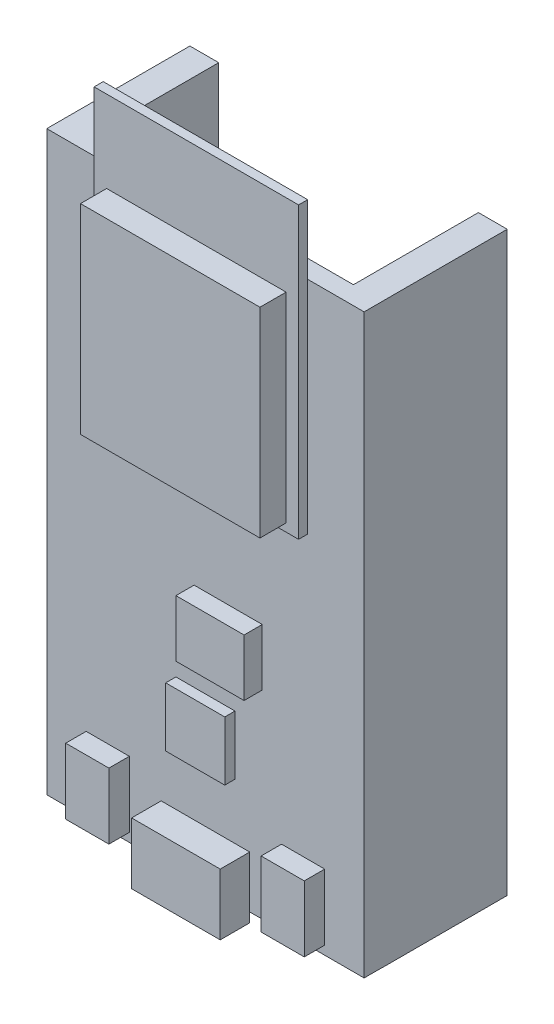
SolidWorks part; units mm, degrees
ref_plane "Front Plane" through (0, 0, 0) normal (0, 0, 1) x (1, 0, 0)
ref_plane "Top Plane" through (0, 0, 0) normal (0, 1, 0) x (1, 0, 0)
ref_plane "Right Plane" through (0, 0, 0) normal (1, 0, 0) x (0, 0, -1)
ref_plane "Plane1" through (0, 0, 10.6) normal (0, 0, 1) x (1, 0, 0)
sketch "Sketch1" plane through (0, 0, 10.6) normal (0, 0, 1) x (1, 0, 0)
  line L1 (-30.97, 19.02) -> (-28.43, 19.02)
  line L2 (-30.97, 19.02) -> (-30.97, 69.82)
  line L3 (-30.97, 69.82) -> (-28.43, 69.82)
  line L4 (-28.43, 19.02) -> (-28.43, 69.82)
  line L5 (-30.97, 19.02) -> (-28.43, 69.82) construction
  line L6 (-30.97, 69.82) -> (-28.43, 19.02) construction
  point P0 (-29.7, 44.42)
extrude "Boss-Extrude1" add sketch "Sketch1" along normal blind 8.5
ref_plane "Plane2" through (0, 0, 19.1) normal (0, 0, 1) x (1, 0, 0)
sketch "Sketch2" plane through (0, 0, 19.1) normal (0, 0, 1) x (1, 0, 0)
  line L1 (-30.97, 19.02) -> (-28.43, 19.02)
  line L2 (-30.97, 19.02) -> (-30.97, 69.82)
  line L3 (-30.97, 69.82) -> (-28.43, 69.82)
  line L4 (-28.43, 19.02) -> (-28.43, 69.82)
  line L5 (-30.97, 19.02) -> (-28.43, 69.82) construction
  line L6 (-30.97, 69.82) -> (-28.43, 19.02) construction
  point P0 (-29.7, 44.42)
extrude "Boss-Extrude2" add sketch "Sketch2" along normal blind 2.5
sketch "Sketch3" plane through (0, 0, 10.6) normal (0, 0, 1) x (1, 0, 0)
  line L1 (-5.57, 19.02) -> (-3.03, 19.02)
  line L2 (-5.57, 19.02) -> (-5.57, 69.82)
  line L3 (-5.57, 69.82) -> (-3.03, 69.82)
  line L4 (-3.03, 19.02) -> (-3.03, 69.82)
  line L5 (-5.57, 19.02) -> (-3.03, 69.82) construction
  line L6 (-5.57, 69.82) -> (-3.03, 19.02) construction
  point P0 (-4.3, 44.42)
extrude "Boss-Extrude3" add sketch "Sketch3" along normal blind 8.5
sketch "Sketch4" plane through (0, 0, 19.1) normal (0, 0, 1) x (1, 0, 0)
  line L1 (-5.57, 19.02) -> (-3.03, 19.02)
  line L2 (-5.57, 19.02) -> (-5.57, 69.82)
  line L3 (-5.57, 69.82) -> (-3.03, 69.82)
  line L4 (-3.03, 19.02) -> (-3.03, 69.82)
  line L5 (-5.57, 19.02) -> (-3.03, 69.82) construction
  line L6 (-5.57, 69.82) -> (-3.03, 19.02) construction
  point P0 (-4.3, 44.42)
extrude "Boss-Extrude4" add sketch "Sketch4" along normal blind 2.5
ref_plane "Plane3" through (0, 0, 21.6) normal (0, 0, 1) x (1, 0, 0)
sketch "Sketch5" plane through (0, 0, 21.6) normal (0, 0, 1) x (1, 0, 0)
  line L1 (-30.97, 19.03) -> (-3.03, 19.03)
  line L2 (-30.97, 19.03) -> (-30.97, 69.82)
  line L3 (-30.97, 69.82) -> (-3.03, 69.82)
  line L4 (-3.03, 19.03) -> (-3.03, 69.82)
  line L5 (-30.97, 19.03) -> (-3.03, 69.82) construction
  line L6 (-30.97, 69.82) -> (-3.03, 19.03) construction
  point P0 (-17, 44.425)
extrude "Boss-Extrude5" add sketch "Sketch5" along normal blind 1.6
ref_plane "Plane4" through (0, 0, 23.2) normal (0, 0, 1) x (1, 0, 0)
sketch "Sketch6" plane through (0, 0, 23.2) normal (0, 0, 1) x (1, 0, 0)
  line L1 (-26, 50.39) -> (-8, 50.39)
  line L2 (-26, 50.39) -> (-26, 75.89)
  line L3 (-26, 75.89) -> (-8, 75.89)
  line L4 (-8, 50.39) -> (-8, 75.89)
  line L5 (-26, 50.39) -> (-8, 75.89) construction
  line L6 (-26, 75.89) -> (-8, 50.39) construction
  point P0 (-17, 63.14)
extrude "Boss-Extrude6" add sketch "Sketch6" along normal blind 0.8
ref_plane "Plane5" through (0, 0, 24) normal (0, 0, 1) x (1, 0, 0)
sketch "Sketch7" plane through (0, 0, 24) normal (0, 0, 1) x (1, 0, 0)
  line L1 (-24.9, 51.09) -> (-9.1, 51.09)
  line L2 (-24.9, 51.09) -> (-24.9, 68.69)
  line L3 (-24.9, 68.69) -> (-9.1, 68.69)
  line L4 (-9.1, 51.09) -> (-9.1, 68.69)
  line L5 (-24.9, 51.09) -> (-9.1, 68.69) construction
  line L6 (-24.9, 68.69) -> (-9.1, 51.09) construction
  point P0 (-17, 59.89)
extrude "Boss-Extrude7" add sketch "Sketch7" along normal blind 2.3
sketch "Sketch8" plane through (0, 0, 23.2) normal (0, 0, 1) x (1, 0, 0)
  line L1 (-20.9, 18.2) -> (-13.1, 18.2)
  line L2 (-20.9, 18.2) -> (-20.9, 23.6)
  line L3 (-20.9, 23.6) -> (-13.1, 23.6)
  line L4 (-13.1, 18.2) -> (-13.1, 23.6)
  line L5 (-20.9, 18.2) -> (-13.1, 23.6) construction
  line L6 (-20.9, 23.6) -> (-13.1, 18.2) construction
  point P0 (-17, 20.9)
extrude "Boss-Extrude8" add sketch "Sketch8" along normal blind 2.6
sketch "Sketch9" plane through (0, 0, 23.2) normal (0, 0, 1) x (1, 0, 0)
  line L1 (-27.5, 19.8) -> (-23.7, 19.8)
  line L2 (-27.5, 19.8) -> (-27.5, 25.6)
  line L3 (-27.5, 25.6) -> (-23.7, 25.6)
  line L4 (-23.7, 19.8) -> (-23.7, 25.6)
  line L5 (-27.5, 19.8) -> (-23.7, 25.6) construction
  line L6 (-27.5, 25.6) -> (-23.7, 19.8) construction
  point P0 (-25.6, 22.7)
extrude "Boss-Extrude9" add sketch "Sketch9" along normal blind 1.8
sketch "Sketch10" plane through (0, 0, 23.2) normal (0, 0, 1) x (1, 0, 0)
  line L1 (-10.3, 19.8) -> (-6.5, 19.8)
  line L2 (-10.3, 19.8) -> (-10.3, 25.6)
  line L3 (-10.3, 25.6) -> (-6.5, 25.6)
  line L4 (-6.5, 19.8) -> (-6.5, 25.6)
  line L5 (-10.3, 19.8) -> (-6.5, 25.6) construction
  line L6 (-10.3, 25.6) -> (-6.5, 19.8) construction
  point P0 (-8.4, 22.7)
extrude "Boss-Extrude10" add sketch "Sketch10" along normal blind 1.8
sketch "Sketch11" plane through (0, 0, 23.2) normal (0, 0, 1) x (1, 0, 0)
  line L1 (-19.6, 28.5) -> (-14.4, 28.5)
  line L2 (-19.6, 28.5) -> (-19.6, 33.7)
  line L3 (-19.6, 33.7) -> (-14.4, 33.7)
  line L4 (-14.4, 28.5) -> (-14.4, 33.7)
  line L5 (-19.6, 28.5) -> (-14.4, 33.7) construction
  line L6 (-19.6, 33.7) -> (-14.4, 28.5) construction
  point P0 (-17, 31.1)
extrude "Boss-Extrude11" add sketch "Sketch11" along normal blind 0.9
sketch "Sketch12" plane through (0, 0, 23.2) normal (0, 0, 1) x (1, 0, 0)
  line L1 (-18, 36.5) -> (-12, 36.5)
  line L2 (-18, 36.5) -> (-18, 41.5)
  line L3 (-18, 41.5) -> (-12, 41.5)
  line L4 (-12, 36.5) -> (-12, 41.5)
  line L5 (-18, 36.5) -> (-12, 41.5) construction
  line L6 (-18, 41.5) -> (-12, 36.5) construction
  point P0 (-15, 39)
extrude "Boss-Extrude12" add sketch "Sketch12" along normal blind 1.6
